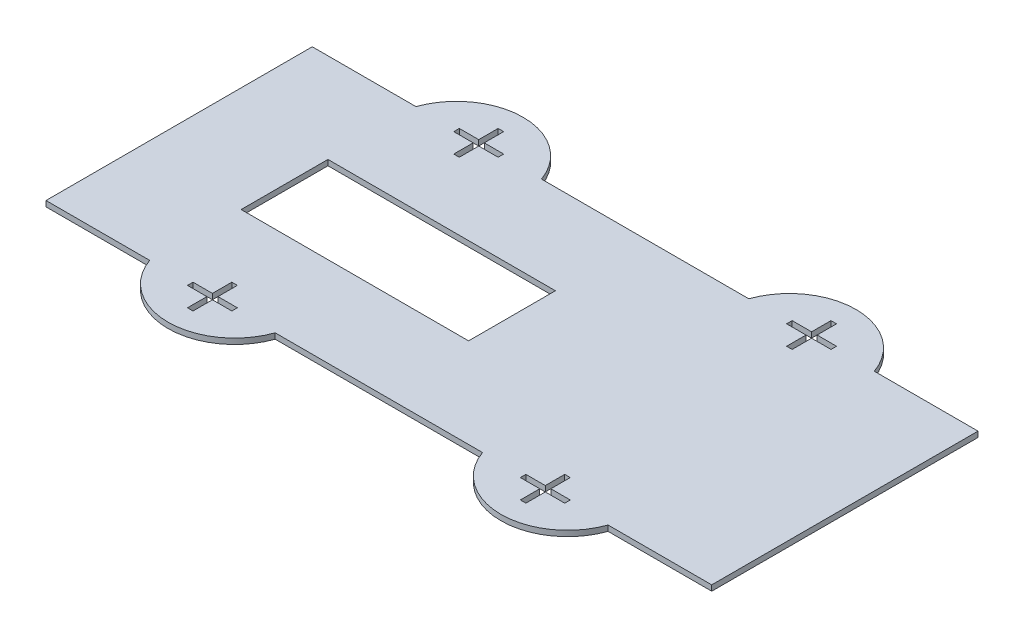
SolidWorks part; units mm, degrees
ref_plane "Front Plane" through (0, 0, 0) normal (0, 0, 1) x (1, 0, 0)
ref_plane "Top Plane" through (0, 0, 0) normal (0, 1, 0) x (1, 0, 0)
ref_plane "Right Plane" through (0, 0, 0) normal (1, 0, 0) x (0, 0, -1)
sketch "Sketch1" plane through (0, 0, 0) normal (0, 1, 0) x (1, 0, 0)
  line L0 (-168.0882, -23.6024) -> (212.9118, -23.6024) construction
  line L1 (-168.0882, 52.5976) -> (212.9118, 52.5976)
  line L2 (-168.0882, 52.5976) -> (-168.0882, -99.8024)
  line L3 (-168.0882, -99.8024) -> (212.9118, -99.8024)
  line L4 (212.9118, 52.5976) -> (212.9118, -99.8024)
  line L5 (-168.0882, -99.8024) -> (212.9118, -99.8024)
  line L6 (-168.0882, -99.8024) -> (-168.0882, -74.4024)
  line L8 (212.9118, -99.8024) -> (212.9118, -74.4024)
  line L9 (-168.0882, -23.6024) -> (-107.7632, -23.6024)
  line L10 (212.9118, 52.5976) -> (212.9118, 27.1976)
  line L11 (-168.0882, 52.5976) -> (212.9118, 52.5976)
  line L12 (-168.0882, 52.5976) -> (-168.0882, 27.1976)
  line L13 (-168.0882, -74.4024) -> (-168.0882, -99.8024)
  line L14 (212.9118, -74.4024) -> (212.9118, -99.8024)
  line L15 (-110.9382, -87.1024) -> (-34.7382, -87.1024)
  line L16 (79.5618, -87.1024) -> (155.7618, -87.1024)
  line L17 (130.3618, -101.3899) -> (130.3618, -98.2149)
  line L19 (22.4118, -23.6024) -> (22.4118, -99.8024) construction
  line L20 (22.4118, -99.8024) -> (22.4118, 52.5976) construction
  line L21 (-110.9382, 39.8976) -> (-34.7382, 39.8976)
  line L22 (79.5618, 39.8976) -> (155.7618, 39.8976)
  line L23 (104.9618, -101.3899) -> (104.9618, -98.2149)
  line L24 (-72.8382, -99.8024) -> (-60.1382, -99.8024)
  line L25 (-72.8382, -99.8024) -> (-85.5382, -99.8024)
  line L26 (-74.4257, -87.1024) -> (-71.2507, -87.1024)
  line L27 (-74.4257, -112.5024) -> (-71.2507, -112.5024)
  line L28 (-71.2507, -112.5024) -> (-71.2507, -87.1024)
  line L29 (-74.4257, -112.5024) -> (-74.4257, -87.1024)
  line L30 (-60.1382, -101.3899) -> (-60.1382, -98.2149)
  line L31 (-85.5382, -101.3899) -> (-85.5382, -98.2149)
  line L32 (-85.5382, -98.2149) -> (-60.1382, -98.2149)
  line L33 (-60.1382, -101.3899) -> (-85.5382, -101.3899)
  line L34 (130.3618, -98.2149) -> (104.9618, -98.2149)
  line L35 (104.9618, -101.3899) -> (130.3618, -101.3899)
  line L36 (119.2493, -112.5024) -> (116.0743, -112.5024)
  line L37 (119.2493, -112.5024) -> (119.2493, -87.1024)
  line L38 (116.0743, -112.5024) -> (116.0743, -87.1024)
  line L39 (119.2493, 65.2976) -> (116.0743, 65.2976)
  line L40 (116.0743, 65.2976) -> (116.0743, 39.8976)
  line L41 (119.2493, 65.2976) -> (119.2493, 39.8976)
  line L42 (130.3618, 54.1851) -> (130.3618, 51.0101)
  line L43 (104.9618, 54.1851) -> (104.9618, 51.0101)
  line L44 (130.3618, 51.0101) -> (104.9618, 51.0101)
  line L45 (104.9618, 54.1851) -> (130.3618, 54.1851)
  line L46 (-74.4257, 65.2976) -> (-71.2507, 65.2976)
  line L47 (-71.2507, 65.2976) -> (-71.2507, 39.8976)
  line L48 (-74.4257, 65.2976) -> (-74.4257, 39.8976)
  line L49 (-34.7382, 39.8976) -> (-110.9382, 39.8976)
  line L50 (-60.1382, 54.1851) -> (-60.1382, 51.0101)
  line L51 (-85.5382, 54.1851) -> (-85.5382, 51.0101)
  line L52 (-60.1382, 54.1851) -> (-85.5382, 54.1851)
  line L53 (-85.5382, 51.0101) -> (-60.1382, 51.0101)
  line L54 (-74.4257, 39.8976) -> (-71.2507, 39.8976)
  line L55 (116.0743, 39.8976) -> (119.2493, 39.8976)
  line L56 (116.0743, -87.1024) -> (119.2493, -87.1024)
  line L57 (-107.7632, -43.4462) -> (-107.7632, -3.7586)
  line L58 (-107.7632, -3.7586) -> (22.4118, -3.7586)
  line L59 (-107.7632, -43.4462) -> (22.4118, -43.4462)
  line L60 (22.4118, -43.4462) -> (22.4118, -3.7586)
  arc A1 (-110.9382, -87.1024) -> (-34.7382, -87.1024) centre (-72.8382, -87.1024) ccw
  arc A2 (-110.9382, 39.8976) -> (-34.7382, 39.8976) centre (-72.8382, 39.8976) cw
  arc A3 (155.7618, -87.1024) -> (79.5618, -87.1024) centre (117.6618, -87.1024) cw
  arc A4 (155.7618, 39.8976) -> (79.5618, 39.8976) centre (117.6618, 39.8976) ccw
  point P32 (-72.8382, -87.1024)
  point P35 (-72.8382, -112.5024)
  point P38 (-60.1382, -99.8024)
  point P41 (-85.5382, -99.8024)
  point P45 (116.0743, -87.1024)
  point P46 (119.2493, -87.1024)
  dimension "D1" = 381
  dimension "D2" = 152.4
  dimension "D3" = 25.4
  dimension "D4" = 60.325
  dimension "D5" = 38.1
  dimension "D6" = 12.7
  dimension "D7" = 12.7
  dimension "D8" = 3.175
  dimension "D9" = 3.175
  dimension "D10" = 3.175
  dimension "D11" = 3.175
  dimension "D12" = 19.8438
  dimension "D13" = 130.175
extrude "Boss-Extrude2" add sketch "Sketch1" along normal blind 3.175
sketch "Sketch2" plane through (0, 3.175, 0) normal (0, 1, 0) x (1, 0, 0)
  line L0 (-107.7632, -3.7586) -> (22.4118, -3.7586)
  line L1 (22.4118, -3.7586) -> (22.4118, -43.4462)
  line L2 (22.4118, -43.4462) -> (-107.7632, -43.4462)
  line L3 (-107.7632, -43.4462) -> (-107.7632, -3.7586)
  line L4 (22.4118, -43.4462) -> (22.4118, -48.4462)
  line L5 (22.4118, -3.7586) -> (22.4118, 1.2414)
  line L6 (22.4118, 1.2414) -> (-107.7632, 1.2414)
  line L7 (-107.7632, 1.2414) -> (-107.7632, -3.7586)
  line L8 (22.4118, -48.4462) -> (-107.7632, -48.4462)
  line L9 (-107.7632, -48.4462) -> (-107.7632, -43.4462)
  dimension "D1" = 5
  dimension "D2" = 5
extrude "Cut-Extrude1" cut sketch "Sketch2" against normal blind 10 contours L9 L8 L4 L2 | L6 L7 L0 L5
